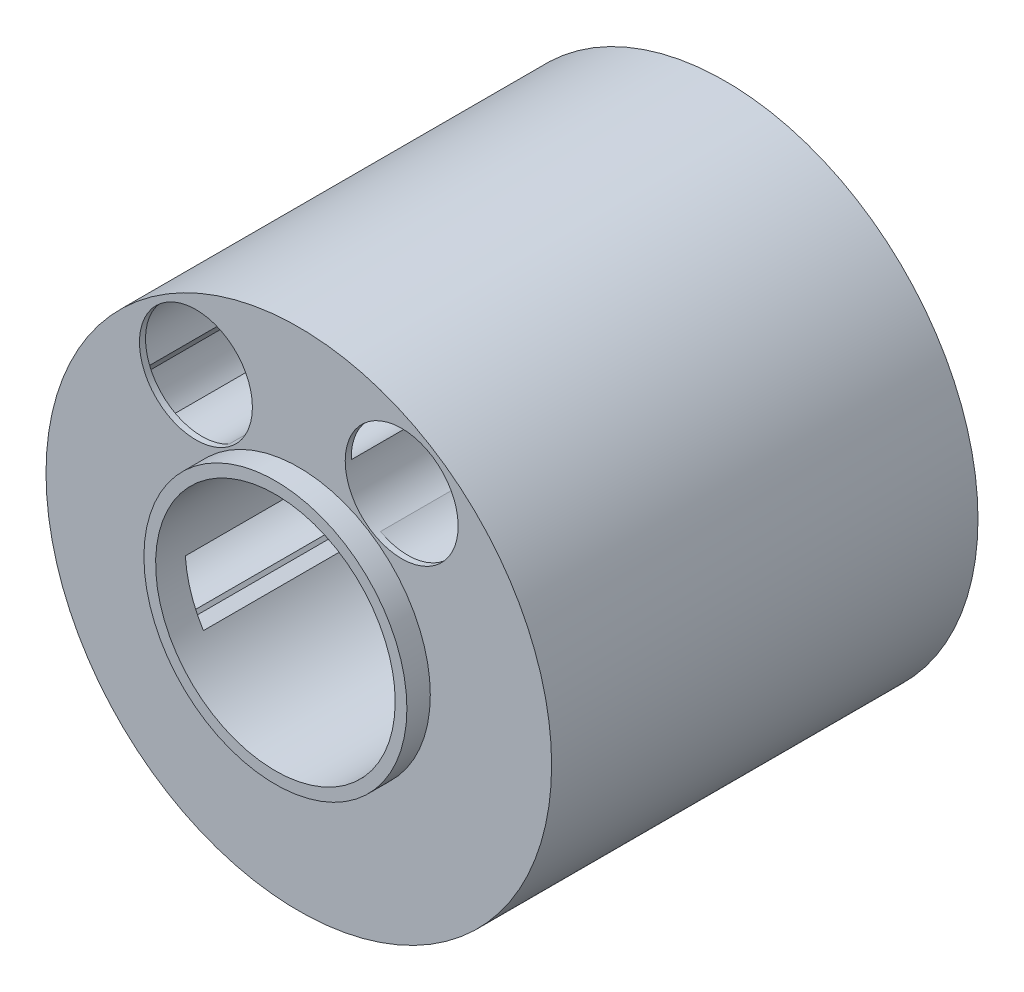
SolidWorks part; units mm, degrees
ref_plane "Front Plane" through (0, 0, 0) normal (0, 0, 1) x (1, 0, 0)
ref_plane "Top Plane" through (0, 0, 0) normal (0, 1, 0) x (1, 0, 0)
ref_plane "Right Plane" through (0, 0, 0) normal (1, 0, 0) x (0, 0, -1)
sketch "Sketch1" plane through (0, 0, 0) normal (0, 0, 1) x (1, 0, 0)
  circle A0 centre (0, 0) radius 43.2
  circle A1 centre (0, 0) radius 20.47
  dimension "D1" = 86.4
  dimension "D2" = 40.94
extrude "Basic Shape" add sketch "Sketch1" along normal blind 67.03
sketch "Sketch2" plane through (0, 0, 0) normal (0, 0, -1) x (-1, 0, 0)
  line L0 (0, 0) -> (0, -20.47) construction
  line L1 (0, -20.47) -> (0, -32.53) construction
  line L2 (0, -32.53) -> (0, -42.18) construction
  line L3 (0, -42.18) -> (0, -43.2) construction
  circle A0 centre (0, -32.53) radius 9.65
  circle A12 centre (0, 0) radius 20.47 construction
  circle A13 centre (0, 0) radius 43.2 construction
  dimension "D1" = 19.3
  dimension "D2" = 1.02
extrude "Battery Slot" cut sketch "Sketch2" against normal blind 67.03
pattern_circular "Battery Slot Pattern" count 10 over 360 about axis through (0, 0, 0) along (0, 0, 1) of "Battery Slot"
sketch "Sketch4" plane through (0, 0, 0) normal (0, 0, -1) x (-1, 0, 0)
  line L0 (0, -22.88) -> (0, -32.53) construction
  line L1 (0, -32.53) -> (0, -42.18) construction
  circle A0 centre (0, 0) radius 29.28
  circle A1 centre (0, 0) radius 35.78
  circle A2 centre (0, -32.53) radius 9.65 construction
  circle A3 centre (0, 0) radius 32.53 construction
  dimension "D1" = 3.25
  dimension "D2" = 3.25
extrude "Bus Slot" cut sketch "Sketch4" against normal blind 67.03
sketch "Sketch5" plane through (0, 0, 0) normal (0, 0, -1) x (-1, 0, 0)
  circle A0 centre (0, 0) radius 20.47
  circle A1 centre (0, 0) radius 22.47
  circle A2 centre (0, 0) radius 43.2
  circle A3 centre (0, 0) radius 42.18
  arc A4 (-12.6443, 33.4713) -> (-27.9258, 22.3687) centre (-19.1207, 26.3173) ccw construction
  circle A5 centre (0, 0) radius 20.47 construction
  circle A6 centre (0, 0) radius 43.2 construction
  circle M4 centre (0, 0) radius 20.47
  dimension "D1" = 2
extrude "Bottom Lip" add sketch "Sketch5" along normal blind 4.8 contours A1 M4 | A2 A3
sketch "Sketch6" plane through (0, 0, 67.03) normal (0, 0, 1) x (1, 0, 0)
  circle A0 centre (0, 0) radius 43.2
  circle A1 centre (0, 0) radius 43.2 construction
extrude "Top Cap" add sketch "Sketch6" along normal blind 1.03
sketch "Sketch7" plane through (0, 0, 68.06) normal (0, 0, 1) x (1, 0, 0)
  line L0 (0, 0) -> (0, 43.2) construction
  line L1 (0, 0) -> (-17.5788, 27.3713) construction
  circle A0 centre (-17.5788, 27.3713) radius 9.65
  circle A1 centre (0, 0) radius 43.2 construction
  dimension "D1" = 19.3
  dimension "D2" = 32.71
  dimension "D3" = 32.53
extrude "Penny Hole" cut sketch "Sketch7" against normal through all
mirror "Penny Hole Mirror" about plane through (0, 0, 0) normal (1, 0, 0) of "Penny Hole"
sketch "Sketch8" plane through (0, 0, 0) normal (0, 0, -1) x (-1, 0, 0)
  line L0 (0, 0) -> (-40.1156, -13.0343) construction
  line L1 (-24.6333, -2.7465) -> (-7.7907, 2.726)
  line L2 (-7.7907, 2.726) -> (-4.7006, -6.7846)
  line L3 (-4.7006, -6.7846) -> (-21.5431, -12.2571)
  arc A0 (-35.7404, -1.6823) -> (-29.9034, -19.6467) centre (-30.9379, -10.0523) ccw construction
  arc A1 (-24.0052, -16.7651) -> (-29.2749, -0.5467) centre (-30.9379, -10.0523) ccw construction
  arc A2 (-24.6333, -2.7465) -> (-21.5431, -12.2571) centre (-30.9379, -10.0523) cw
  arc A3 (-24.0052, -16.7651) -> (-29.2749, -0.5467) centre (-30.9379, -10.0523) ccw construction
  point P12 (-6.2456, -2.0293)
  dimension "D1" = 10
  dimension "D2" = 6.5671
extrude "Wire Slit" cut sketch "Sketch8" against normal up to surface (67.03 mm away) and the other way through all up to face at (0, 32.579, 67.03)
mirror "Wire Slit Mirror" about plane through (0, 0, 0) normal (1, 0, 0) of "Wire Slit"
sketch "Sketch9" plane through (0, 0, 67.03) normal (0, 0, -1) x (-1, 0, 0)
  circle A0 centre (0, 0) radius 20.47
  arc A1 (20.4235, -1.3787) -> (-20.4235, -1.3787) centre (0, 0) ccw construction
extrude "Re-Cut Basic Shape" cut sketch "Sketch9" against normal through all
sketch "Sketch10" plane through (0, 0, 68.06) normal (0, 0, 1) x (1, 0, 0)
  circle A0 centre (0, 0) radius 20.47
  circle A1 centre (0, 0) radius 22.47
  circle A2 centre (0, 0) radius 20.47 construction
  dimension "D1" = 2
extrude "Top Lip" add sketch "Sketch10" along normal blind 4
